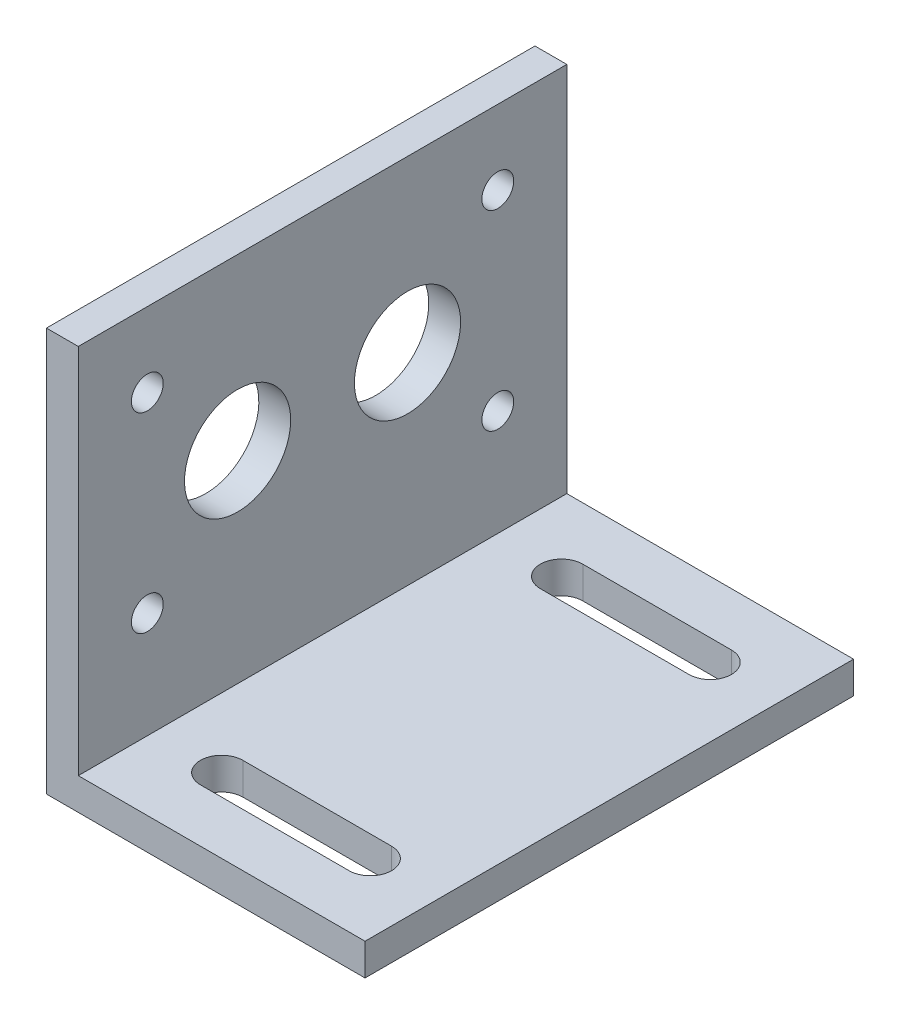
SolidWorks part; units mm, degrees
ref_plane "前视基准面" through (0, 0, 0) normal (0, 0, 1) x (1, 0, 0)
ref_plane "上视基准面" through (0, 0, 0) normal (0, 1, 0) x (1, 0, 0)
ref_plane "右视基准面" through (0, 0, 0) normal (1, 0, 0) x (0, 0, -1)
sketch "草图1" plane through (0, 0, 0) normal (0, 0, 1) x (1, 0, 0)
  line L0 (0, 0) -> (30, 0)
  line L1 (30, 0) -> (30, 3)
  line L2 (30, 3) -> (3, 3)
  line L3 (3, 3) -> (3, 38)
  line L4 (3, 38) -> (0, 38)
  line L5 (0, 38) -> (0, 0)
  dimension "D1" = 38
  dimension "D2" = 30
  dimension "D3" = 3
  dimension "D4" = 3
extrude "凸台-拉伸1" add sketch "草图1" along normal blind 46
sketch "草图2" plane through (3, 0, 0) normal (1, 0, 0) x (0, 0, -1)
  line L0 (-46, 3) -> (-46, 38) construction
  line L4 (-46, 38) -> (0, 38) construction
  line L5 (0, 3) -> (0, 38) construction
  circle A0 centre (-39.5, 31) radius 1.5
  circle A1 centre (-39.5, 13) radius 1.5
  circle A2 centre (-6.5, 31) radius 1.5
  circle A3 centre (-6.5, 13) radius 1.5
  circle A6 centre (-31, 22) radius 5
  circle A7 centre (-15, 22) radius 5
  dimension "D7" = 3
  dimension "D8" = 6.5
  dimension "D9" = 10
  dimension "D1" = 15
  dimension "D2" = 15
  dimension "D3" = 18
  dimension "D4" = 9
  dimension "D5" = 33
  dimension "D6" = 16
extrude "切除-拉伸1" cut sketch "草图2" against normal blind 56
sketch "草图3" plane through (0, 3, 0) normal (0, 1, 0) x (1, 0, 0)
  line L0 (9.5, -7) -> (23.5, -7) construction
  line L1 (9.5, -5) -> (23.5, -5)
  line L2 (9.5, -9) -> (23.5, -9)
  line L3 (9.5, -39) -> (23.5, -39) construction
  line L4 (9.5, -37) -> (23.5, -37)
  line L5 (9.5, -41) -> (23.5, -41)
  line L7 (30, -46) -> (30, 0) construction
  arc A0 (9.5, -5) -> (9.5, -9) centre (9.5, -7) ccw
  arc A1 (23.5, -9) -> (23.5, -5) centre (23.5, -7) ccw
  arc A2 (9.5, -37) -> (9.5, -41) centre (9.5, -39) ccw
  arc A3 (23.5, -41) -> (23.5, -37) centre (23.5, -39) ccw
  point P2 (16.5, -7)
  point P7 (16.5, -39)
  point P18 (30, -23)
  dimension "D3" = 2
  dimension "D1" = 14
  dimension "D2" = 6.5
  dimension "D4" = 32
  dimension "D5" = 16
extrude "切除-拉伸2" cut sketch "草图3" against normal blind 56
